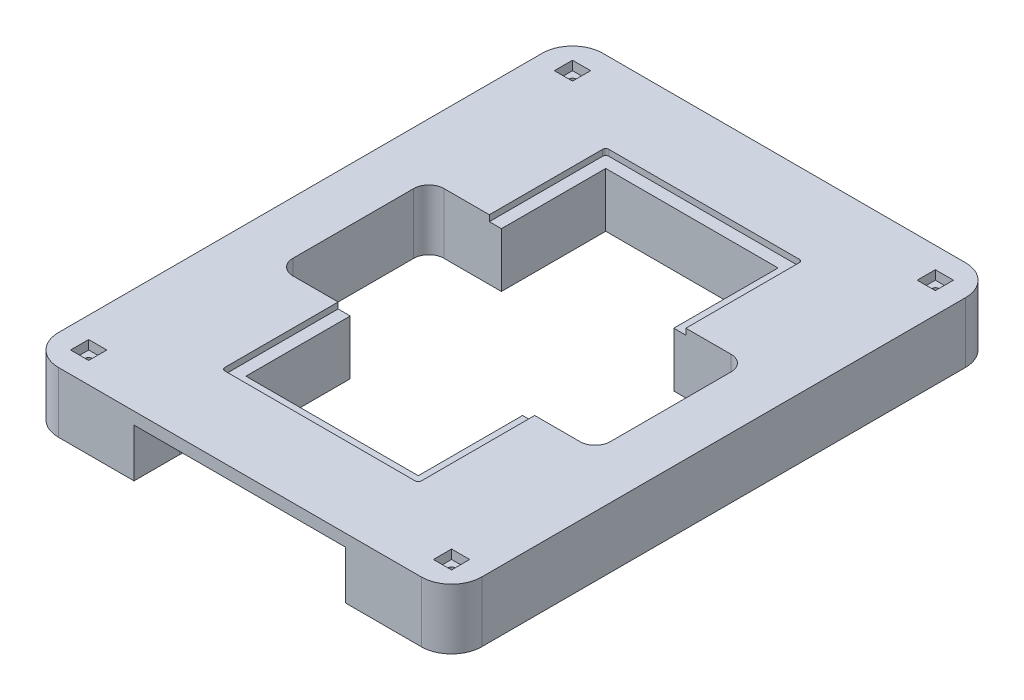
SolidWorks part; units mm, degrees
ref_plane "前视基准面" through (0, 0, 0) normal (0, 0, 1) x (1, 0, 0)
ref_plane "上视基准面" through (0, 0, 0) normal (0, 1, 0) x (1, 0, 0)
ref_plane "右视基准面" through (0, 0, 0) normal (1, 0, 0) x (0, 0, -1)
sketch "草图1" plane through (0, 0, 0) normal (0, 1, 0) x (1, 0, 0)
  line L1 (100, -100) -> (-100, -100)
  line L2 (100, -100) -> (100, 100)
  line L3 (100, 100) -> (-100, 100)
  line L4 (-100, -100) -> (-100, 100)
  line L5 (100, -100) -> (-100, 100) construction
  line L6 (100, 100) -> (-100, -100) construction
  point P1 (0, 0)
  dimension "D1" = 200
  dimension "D2" = 200
extrude "凸台-拉伸1" add sketch "草图1" along normal blind 20
sketch "草图2" plane through (0, 20, 0) normal (0, 1, 0) x (1, 0, 0)
  line L1 (70, -90) -> (-70, -90)
  line L2 (70, -90) -> (70, 90)
  line L3 (70, 90) -> (-70, 90)
  line L4 (-70, -90) -> (-70, 90)
  line L5 (70, -90) -> (-70, 90) construction
  line L6 (70, 90) -> (-70, -90) construction
  line L7 (100, -100) -> (-100, -100)
  line L8 (100, -100) -> (100, 100)
  line L9 (100, 100) -> (-100, 100)
  line L10 (-100, -100) -> (-100, 100)
  line L11 (100, -100) -> (-100, 100) construction
  line L12 (100, 100) -> (-100, -100) construction
  point P0 (0, 0)
  point P6 (0, 0)
  dimension "D1" = 140
  dimension "D2" = 180
extrude "切除-拉伸2" cut sketch "草图2" against normal through all
fillet "圆角1" radius 10 1 edges at (-70, 10, -90)
fillet "圆角2" radius 10 1 edges at (70, 10, -90)
fillet "圆角3" radius 10 1 edges at (70, 10, 90)
fillet "圆角4" radius 10 1 edges at (-70, 10, 90)
sketch "草图4" plane through (0, 0, 0) normal (0, -1, 0) x (1, 0, 0)
  line L5 (-60, 90) -> (60, 90) construction
  line L82 (-70, -80) -> (-70, 80) construction
  line L83 (-59.5, 84.9749) -> (-59.5, 86)
  line L95 (-59.5, 74) -> (-60.5, 74)
  line L97 (-59.5, 74) -> (-59.5, 75.0251)
  line L102 (-59.5, 86) -> (-60.5, 86)
  line L103 (-60.5, 74) -> (-60.5, 75.0251)
  line L108 (-66, 79.5) -> (-64.9749, 79.5)
  line L109 (-66, 79.5) -> (-66, 80.5)
  line L110 (-66, 80.5) -> (-64.9749, 80.5)
  line L111 (-54, 79.5) -> (-54, 80.5)
  line L115 (-60.5, 84.9749) -> (-60.5, 86)
  line L116 (-55.0251, 80.5) -> (-54, 80.5)
  line L120 (-55.0251, 79.5) -> (-54, 79.5)
  arc A5 (-60.5, 84.9749) -> (-64.9749, 80.5) centre (-60, 80) ccw
  arc A6 (-55.0251, 80.5) -> (-59.5, 84.9749) centre (-60, 80) ccw
  arc A7 (-59.5, 75.0251) -> (-55.0251, 79.5) centre (-60, 80) ccw
  arc A8 (-64.9749, 79.5) -> (-60.5, 75.0251) centre (-60, 80) ccw
  point P0 (0, 0)
  point P2 (-60, 80)
  dimension "D3" = 1
  dimension "D4" = 12
  dimension "D1" = 10
  dimension "D2" = 10
  dimension "D5" = 1
  dimension "D6" = 12
extrude "切除-拉伸4" cut sketch "草图4" against normal blind 5
mirror "镜向3" about plane through (0, 0, 0) normal (1, 0, 0) of "切除-拉伸4" second plane through (0, 0, 0) second plane normal (0, 0, 1)
sketch "草图5" plane through (0, 0, 0) normal (0, -1, 0) x (1, 0, 0)
  line L1 (60, -80) -> (-60, -80) construction
  line L2 (60, -80) -> (60, 80) construction
  line L3 (60, 80) -> (-60, 80) construction
  line L4 (-60, -80) -> (-60, 80) construction
  line L5 (60, -80) -> (-60, 80) construction
  line L6 (60, 80) -> (-60, -80) construction
  circle A0 centre (-60, 80) radius 5
  point P0 (0, 0)
  dimension "D3" = 10
  dimension "D1" = 120
  dimension "D2" = 160
extrude "切除-拉伸5" cut sketch "草图5" against normal blind 6.2
sketch "草图7" plane through (0, 0, 0) normal (0, -1, 0) x (1, 0, 0)
  line L0 (-60, 90) -> (60, 90) construction
  line L1 (35, 110) -> (-35, 110)
  line L2 (35, 110) -> (35, 75)
  line L3 (30, 70) -> (-30, 70)
  line L4 (-35, 110) -> (-35, 75)
  line L5 (35, 110) -> (-35, 70) construction
  line L6 (35, 70) -> (-35, 110) construction
  arc A0 (-30, 70) -> (-35, 75) centre (-30, 75) cw
  arc A1 (30, 70) -> (35, 75) centre (30, 75) ccw
  point P0 (0, 90)
  dimension "D3" = 5
  dimension "D4" = 5
  dimension "D1" = 70
  dimension "D2" = 40
extrude "切除-拉伸7" cut sketch "草图7" against normal blind 16
mirror "镜向6" about plane through (0, 0, 0) normal (0, 0, 1) of "切除-拉伸7"
sketch "草图8" plane through (0, 0, 0) normal (0, -1, 0) x (1, 0, 0)
  line L5 (40.5, -40.5) -> (-40.5, -40.5) construction
  line L6 (40.5, -40.5) -> (40.5, 40.5) construction
  line L7 (40.5, 40.5) -> (-40.5, 40.5) construction
  line L8 (-40.5, -40.5) -> (-40.5, 40.5) construction
  line L9 (40.5, -40.5) -> (-40.5, 40.5) construction
  line L10 (40.5, 40.5) -> (-40.5, -40.5) construction
  circle A4 centre (-40.5, 40.5) radius 4.1
  point P0 (0, 0)
  dimension "D1" = 81
  dimension "D2" = 81
extrude "切除-拉伸8" cut sketch "草图8" against normal blind 4
draft "拔模2" type of draft neutral plane draft angle 10 faces to draft 1 face at (-40.5, 4, 36.4) neutral plane through (-40.5, 4, 40.5) neutral plane normal (0, -1, 0) parameters "D1"=10
mirror "镜向10" about plane through (0, 0, 0) normal (1, 0, 0) of "拔模2", "切除-拉伸8"
mirror "镜向11" about plane through (0, 0, 0) normal (0, 0, 1) of "切除-拉伸8", "拔模2"
sketch "草图14" plane through (0, 20, 0) normal (0, 1, 0) x (1, 0, 0)
  line L1 (60, -80) -> (-60, -80) construction
  line L2 (60, -80) -> (60, 80) construction
  line L3 (60, 80) -> (-60, 80) construction
  line L4 (-60, -80) -> (-60, 80) construction
  line L5 (60, -80) -> (-60, 80) construction
  line L6 (60, 80) -> (-60, -80) construction
  line L7 (-57, 77) -> (-63, 77)
  line L8 (-57, 77) -> (-57, 83)
  line L9 (-57, 83) -> (-63, 83)
  line L10 (-63, 77) -> (-63, 83)
  line L11 (-57, 77) -> (-63, 83) construction
  line L12 (-57, 83) -> (-63, 77) construction
  point P0 (0, 0)
  dimension "D1" = 120
  dimension "D2" = 160
  dimension "D3" = 6
  dimension "D4" = 6
extrude "切除-拉伸9" cut sketch "草图14" against normal blind 3
mirror "镜向12" about plane through (0, 0, 0) normal (1, 0, 0) of "切除-拉伸9" second plane through (0, 0, 0) second plane normal (0, 0, 1)
sketch "草图21" plane through (0, 20, 0) normal (0, 1, 0) x (1, 0, 0)
  line L1 (31.5, -63.5) -> (-31.5, -63.5)
  line L2 (32.5, -62.5) -> (32.5, 62.5)
  line L3 (31.5, 63.5) -> (-31.5, 63.5)
  line L4 (-32.5, -62.5) -> (-32.5, 62.5)
  line L5 (32.5, -63.5) -> (-32.5, 63.5) construction
  line L6 (32.5, 63.5) -> (-32.5, -63.5) construction
  arc A0 (-31.5, -63.5) -> (-32.5, -62.5) centre (-31.5, -62.5) cw
  arc A1 (32.5, -62.5) -> (31.5, -63.5) centre (31.5, -62.5) cw
  arc A2 (31.5, 63.5) -> (32.5, 62.5) centre (31.5, 62.5) cw
  arc A3 (-32.5, 62.5) -> (-31.5, 63.5) centre (-31.5, 62.5) cw
  point P0 (0, 0)
  dimension "D3" = 1
  dimension "D1" = 65
  dimension "D2" = 127
extrude "切除-拉伸14" cut sketch "草图21" against normal blind 2
sketch "草图22" plane through (0, 18, 0) normal (0, 1, 0) x (1, 0, 0)
  line L1 (28.5, -59.5) -> (-28.5, -59.5)
  line L2 (28.5, -59.5) -> (28.5, 59.5)
  line L3 (28.5, 59.5) -> (-28.5, 59.5)
  line L4 (-28.5, -59.5) -> (-28.5, 59.5)
  line L5 (28.5, -59.5) -> (-28.5, 59.5) construction
  line L6 (28.5, 59.5) -> (-28.5, -59.5) construction
  point P0 (0, 0)
  dimension "D1" = 57
  dimension "D2" = 119
extrude "切除-拉伸15" cut sketch "草图22" against normal through all
sketch "草图23" plane through (0, 20, 0) normal (0, 1, 0) x (1, 0, 0)
  line L1 (47.5, -25) -> (-47.5, -25)
  line L2 (52.5, -20) -> (52.5, 20)
  line L3 (47.5, 25) -> (-47.5, 25)
  line L4 (-52.5, -20) -> (-52.5, 20)
  line L5 (52.5, -25) -> (-52.5, 25) construction
  line L6 (52.5, 25) -> (-52.5, -25) construction
  arc A0 (-52.5, 20) -> (-47.5, 25) centre (-47.5, 20) cw
  arc A1 (52.5, 20) -> (47.5, 25) centre (47.5, 20) ccw
  arc A2 (-47.5, -25) -> (-52.5, -20) centre (-47.5, -20) cw
  arc A3 (52.5, -20) -> (47.5, -25) centre (47.5, -20) cw
  point P0 (0, 0)
  dimension "D3" = 5
  dimension "D4" = 5
  dimension "D5" = 5
  dimension "D1" = 50
  dimension "D2" = 105
extrude "切除-拉伸16" cut sketch "草图23" against normal through all
sketch "草图24" plane through (0, 0, 0) normal (0, -1, 0) x (1, 0, 0)
  line L0 (-60, 90) -> (-35, 90) construction
  line L1 (-70, -80) -> (-70, 80) construction
  circle A0 centre (-60, 80) radius 1.2
  dimension "D1" = 10
  dimension "D2" = 10
extrude "切除-拉伸17" cut sketch "草图24" against normal through all
mirror "镜向13" about plane through (0, 0, 0) normal (0, 0, 1) of "切除-拉伸17" second plane through (0, 0, 0) second plane normal (1, 0, 0)
